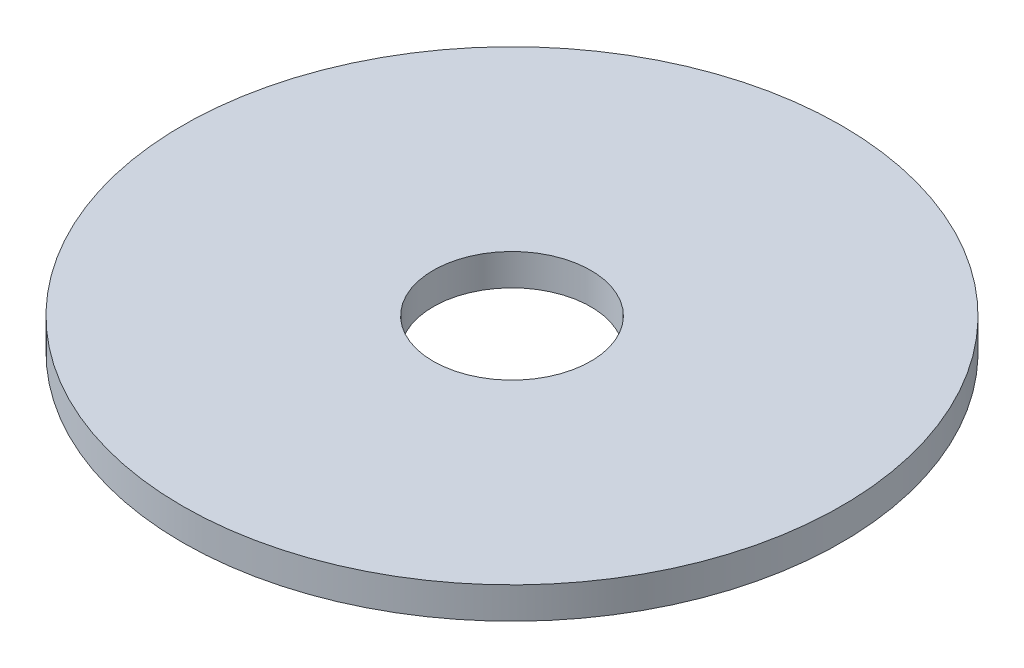
SolidWorks part; units mm, degrees
material "ASTM A36 Steel"
ref_plane "Front Plane" through (0, 0, 0) normal (0, 0, 1) x (1, 0, 0)
ref_plane "Top Plane" through (0, 0, 0) normal (0, 1, 0) x (1, 0, 0)
ref_plane "Right Plane" through (0, 0, 0) normal (1, 0, 0) x (0, 0, -1)
sketch "Sketch1" plane through (0, 0, 0) normal (0, 1, 0) x (1, 0, 0)
  circle A0 centre (0, 0) radius 104.55
  circle A1 centre (0, 0) radius 25
  dimension "D1" = 209.1
  dimension "D2" = 50
extrude "Boss-Extrude1" add sketch "Sketch1" along normal blind 10
